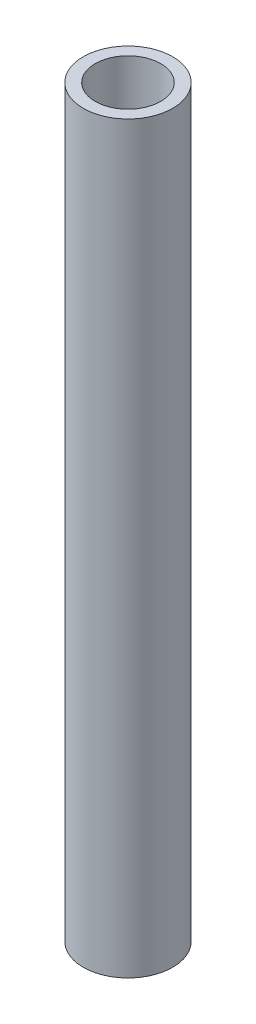
SolidWorks part; units mm, degrees
material "AISI 316 Stainless Steel Sheet (SS)"
ref_plane "Front Plane" through (0, 0, 0) normal (0, 0, 1) x (1, 0, 0)
ref_plane "Top Plane" through (0, 0, 0) normal (0, 1, 0) x (1, 0, 0)
ref_plane "Right Plane" through (0, 0, 0) normal (1, 0, 0) x (0, 0, -1)
sketch "Sketch1" plane through (0, 0, 0) normal (0, 1, 0) x (1, 0, 0)
  circle A0 centre (0, 0) radius 0.4508
  circle A1 centre (0, 0) radius 0.3302
  dimension "D1" = 0.6604
  dimension "D2" = 0.9017
extrude "Boss-Extrude1" add sketch "Sketch1" along normal blind 7.5 contours A0 A1
